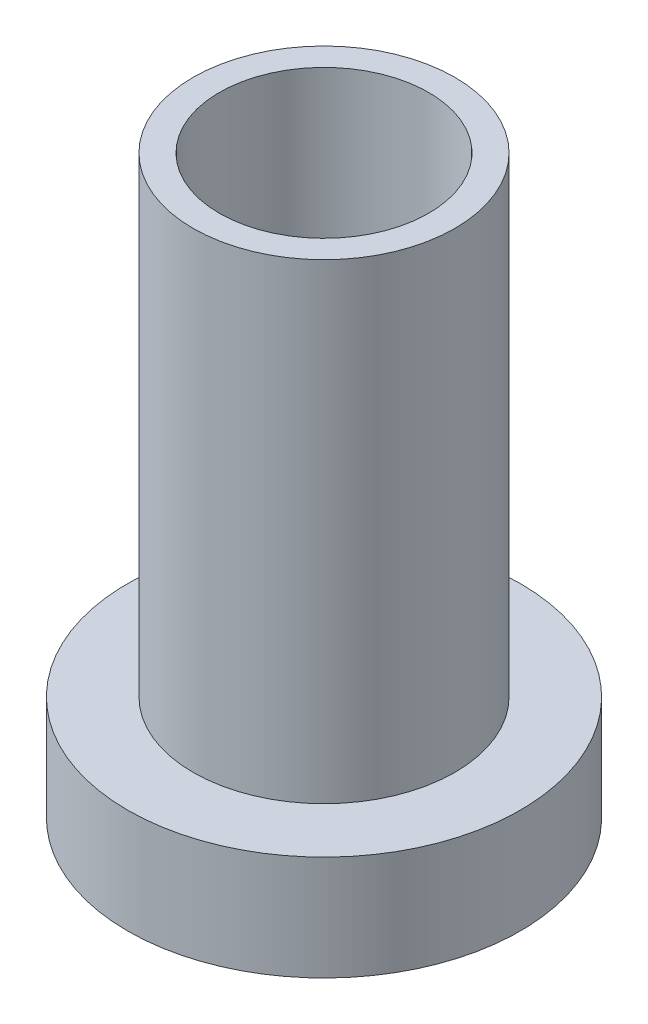
SolidWorks part; units mm, degrees
ref_plane "Спереди" through (0, 0, 0) normal (0, 0, 1) x (1, 0, 0)
ref_plane "Сверху" through (0, 0, 0) normal (0, 1, 0) x (1, 0, 0)
ref_plane "Справа" through (0, 0, 0) normal (1, 0, 0) x (0, 0, -1)
sketch "Эскиз1" plane through (0, 0, 0) normal (0, 1, 0) x (1, 0, 0)
  circle A0 centre (0, 0) radius 7.5
  dimension "D1" = 15
extrude "Бобышка-Вытянуть1" add sketch "Эскиз1" along normal blind 4
sketch "Эскиз3" plane through (0, 4, 0) normal (0, 1, 0) x (1, 0, 0)
  circle A0 centre (0, 0) radius 5
  dimension "D1" = 10
extrude "Бобышка-Вытянуть2" add sketch "Эскиз3" along normal blind 18
sketch "Эскиз4" plane through (0, 22, 0) normal (0, 1, 0) x (1, 0, 0)
  circle A0 centre (0, 0) radius 4
  dimension "D1" = 8
extrude "Вырез-Вытянуть1" cut sketch "Эскиз4" against normal blind 18
